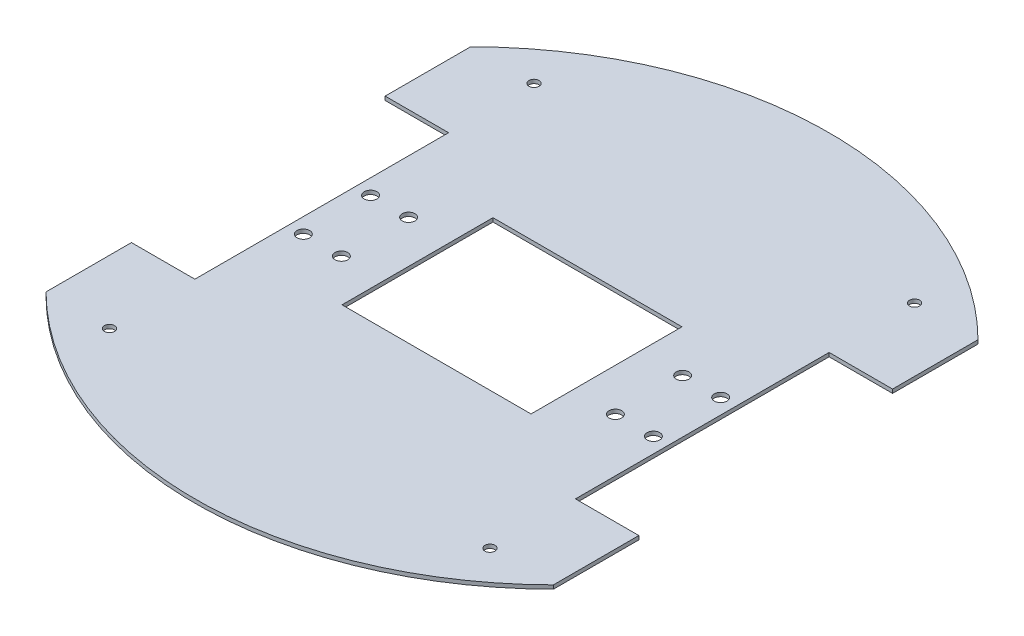
SolidWorks part; units mm, degrees
ref_plane "Front Plane" through (0, 0, 0) normal (0, 0, 1) x (1, 0, 0)
ref_plane "Top Plane" through (0, 0, 0) normal (0, 1, 0) x (1, 0, 0)
ref_plane "Right Plane" through (0, 0, 0) normal (1, 0, 0) x (0, 0, -1)
sketch "Sketch3" plane through (0, 0, 0) normal (0, 1, 0) x (1, 0, 0)
  line L0 (-150, 100) -> (-200, 100)
  line L5 (-200, 100) -> (-150, 100) construction
  line L7 (200, -100) -> (150, -100) construction
  line L8 (-150, 100) -> (-150, -100)
  line L10 (150, -100) -> (150, 100)
  line L11 (150, 100) -> (200, 100)
  line L12 (200, 100) -> (200, 167.3599)
  line L13 (-150, -100) -> (-200, -100)
  line L14 (-200, -100) -> (-200, -167.3599)
  line L15 (-200, 100) -> (-200, 167.3599)
  line L16 (150, -100) -> (200, -100)
  line L17 (200, -100) -> (200, -167.3599)
  line L18 (150, 100) -> (200, 100) construction
  line L19 (-150, -100) -> (-200, -100) construction
  arc A0 (-200, -167.3599) -> (200, -167.3599) centre (0, 33.3333) ccw
  arc A1 (-200, 167.3599) -> (200, 167.3599) centre (0, -33.3333) cw
  point P0 (0, 0)
extrude "Boss-Extrude1" add sketch "Sketch3" along normal blind 3
sketch "Sketch4" plane through (0, 3, 0) normal (0, 1, 0) x (1, 0, 0)
  line L0 (0, 250) -> (0, -250) construction
  line L1 (-150, 0) -> (150, 0) construction
  line L2 (-150, 100) -> (-150, -100) construction
  line L3 (150, -100) -> (150, 100) construction
  circle A0 centre (-150, 167.3599) radius 4
  arc A1 (200, 167.3599) -> (-200, 167.3599) centre (0, -33.3333) ccw construction
  arc A2 (-200, -167.3599) -> (200, -167.3599) centre (0, 33.3333) ccw construction
  circle A3 centre (150, 167.3599) radius 4
  circle A4 centre (150, -167.3599) radius 4
  circle A5 centre (-150, -167.3599) radius 4
extrude "Cut-Extrude1" cut sketch "Sketch4" against normal blind 10
sketch "Sketch6" plane through (0, 0, 0) normal (0, -1, 0) x (1, 0, 0)
  line L1 (74.5, -59.5) -> (-74.5, -59.5)
  line L2 (74.5, -59.5) -> (74.5, 59.5)
  line L3 (74.5, 59.5) -> (-74.5, 59.5)
  line L4 (-74.5, -59.5) -> (-74.5, 59.5)
  line L5 (74.5, -59.5) -> (-74.5, 59.5) construction
  line L6 (74.5, 59.5) -> (-74.5, -59.5) construction
  point P0 (0, 0)
extrude "Cut-Extrude2" cut sketch "Sketch6" against normal blind 10
sketch "Sketch7" plane through (0, 0, 0) normal (0, -1, 0) x (1, 0, 0)
  line L0 (-150, 0) -> (-150, 26.5)
  line L1 (-150, -100) -> (-150, 100) construction
  line L2 (-150, 26.5) -> (-138, 26.5)
  line L3 (-138, 26.5) -> (-108, 26.5)
  line L4 (-150, 0) -> (150, 0) construction
  line L5 (150, 100) -> (150, -100) construction
  line L6 (0, 250) -> (0, -250) construction
  line L7 (138, 26.5) -> (108, 26.5)
  line L8 (138, -26.5) -> (108, -26.5)
  line L9 (-138, -26.5) -> (-108, -26.5)
  line L10 (-150, -26.5) -> (-138, -26.5)
  circle A0 centre (-138, 26.5) radius 5
  circle A1 centre (-108, 26.5) radius 5
  arc A2 (200, 167.3599) -> (-200, 167.3599) centre (0, -33.3333) ccw construction
  arc A3 (-200, -167.3599) -> (200, -167.3599) centre (0, 33.3333) ccw construction
  circle A4 centre (108, 26.5) radius 5
  circle A5 centre (138, 26.5) radius 5
  circle A6 centre (138, -26.5) radius 5
  circle A7 centre (108, -26.5) radius 5
  circle A8 centre (-108, -26.5) radius 5
  circle A9 centre (-138, -26.5) radius 5
extrude "Cut-Extrude3" cut sketch "Sketch7" against normal blind 10
